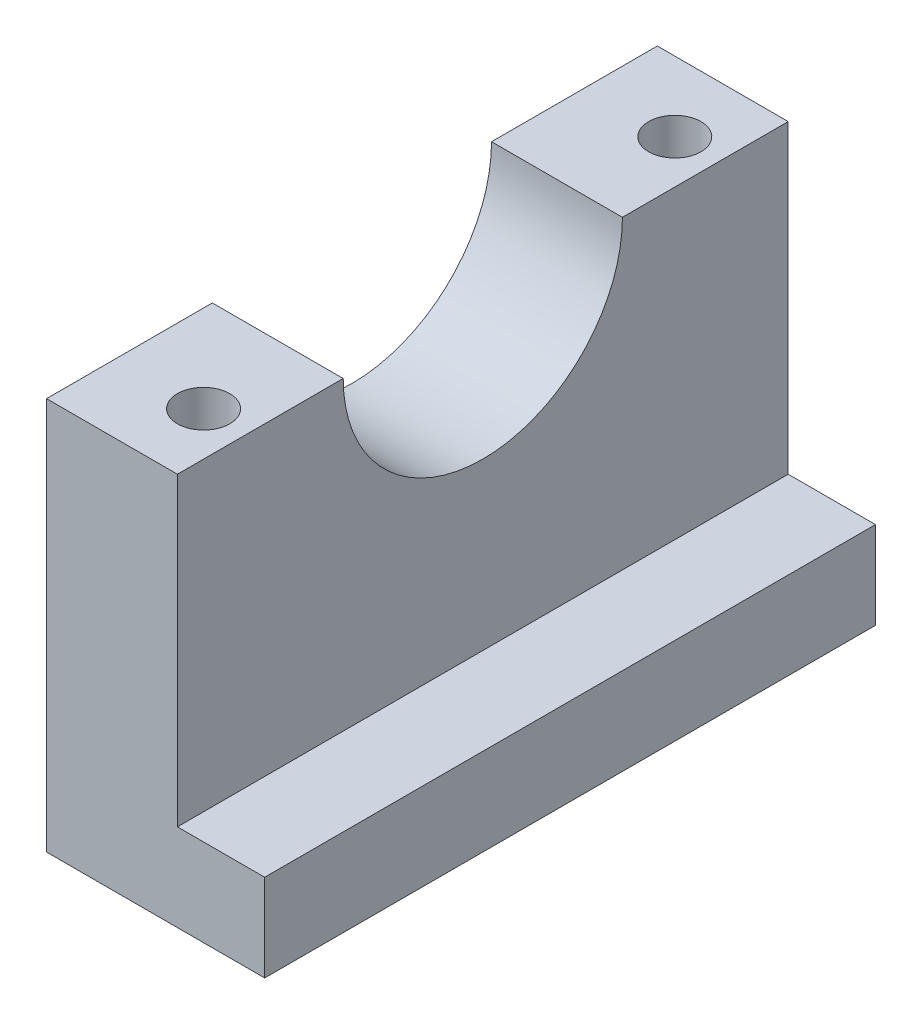
SolidWorks part; units mm, degrees
material "Plain Carbon Steel"
ref_plane "Front Plane" through (0, 0, 0) normal (0, 0, 1) x (1, 0, 0)
ref_plane "Top Plane" through (0, 0, 0) normal (0, 1, 0) x (1, 0, 0)
ref_plane "Right Plane" through (0, 0, 0) normal (1, 0, 0) x (0, 0, -1)
sketch "Sketch1" plane through (0, 0, 0) normal (1, 0, 0) x (0, 0, -1)
  line L0 (16, 45) -> (35, 45)
  line L1 (-35, 0) -> (35, 0)
  line L2 (-35, 0) -> (-35, 45)
  line L3 (-35, 45) -> (-16, 45)
  line L4 (35, 0) -> (35, 45)
  arc A0 (-16, 45) -> (16, 45) centre (0, 45) ccw
  point P5 (0, 0)
  dimension "D3" = 32
  dimension "D1" = 45
  dimension "D2" = 70
extrude "Boss-Extrude1" add sketch "Sketch1" along normal blind 15
sketch "Sketch2" plane through (0, 0, 0) normal (0, 1, 0) x (1, 0, 0)
  line L0 (15, -35) -> (0, -35) construction
  line L1 (15, 35) -> (0, 35) construction
  line L2 (0, -35) -> (0, 35) construction
  circle A0 centre (10, -27) radius 3
  circle A1 centre (10, 27) radius 3
  dimension "D1" = 6
  dimension "D2" = 8
  dimension "D3" = 8
  dimension "D4" = 10
extrude "Cut-Extrude1" cut sketch "Sketch2" along normal through all
sketch "Sketch3" plane through (15, 0, 0) normal (1, 0, 0) x (0, 0, -1)
  line L0 (35, 0) -> (35, 45) construction
  line L1 (-35, 0) -> (35, 0)
  line L2 (-35, 0) -> (-35, 10)
  line L3 (-35, 10) -> (35, 10)
  line L4 (35, 0) -> (35, 10)
  dimension "D1" = 10
extrude "Boss-Extrude2" add sketch "Sketch3" along normal blind 10
sketch "Sketch4" plane through (0, 0, 0) normal (0, -1, 0) x (1, 0, 0)
  circle A0 centre (10, 27) radius 6
  circle A1 centre (10, -27) radius 6
  dimension "D1" = 12
extrude "Cut-Extrude2" cut sketch "Sketch4" against normal blind 7
